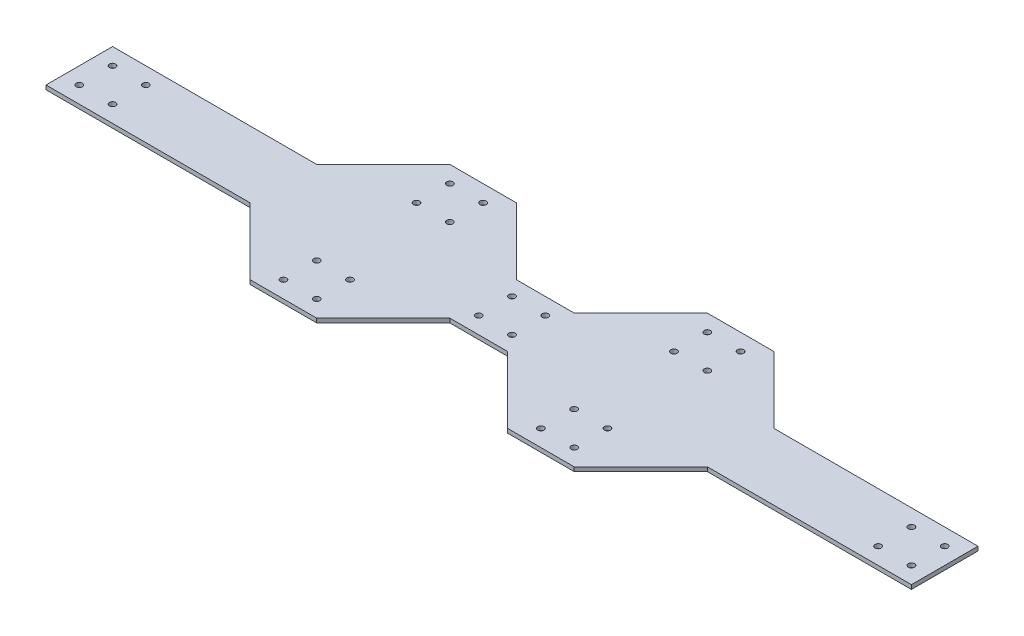
SolidWorks part; units mm, degrees
ref_plane "Front Plane" through (0, 0, 0) normal (0, 0, 1) x (1, 0, 0)
ref_plane "Top Plane" through (0, 0, 0) normal (0, 1, 0) x (1, 0, 0)
ref_plane "Right Plane" through (0, 0, 0) normal (1, 0, 0) x (0, 0, -1)
sketch "Sketch2" plane through (0, 0, 0) normal (0, 1, 0) x (1, 0, 0)
  line L0 (0, 0) -> (0, 50000) construction
  line L1 (22.0266, 25.4) -> (72.8266, 76.2)
  line L2 (72.8266, 76.2) -> (123.6266, 76.2)
  line L3 (123.6266, 76.2) -> (174.4266, 25.4)
  line L4 (174.4266, 25.4) -> (330.2, 25.4)
  line L5 (330.2, 25.4) -> (330.2, -25.4)
  line L6 (330.2, -25.4) -> (174.4266, -25.4)
  line L7 (174.4266, -25.4) -> (123.6266, -76.2)
  line L8 (123.6266, -76.2) -> (72.8266, -76.2)
  line L9 (72.8266, -76.2) -> (22.0266, -25.4)
  line L10 (22.0266, -25.4) -> (-22.0266, -25.4)
  line L11 (22.0266, 25.4) -> (-22.0266, 25.4)
  line L12 (-72.8266, -76.2) -> (-22.0266, -25.4)
  line L13 (-123.6266, -76.2) -> (-72.8266, -76.2)
  line L14 (-174.4266, -25.4) -> (-123.6266, -76.2)
  line L15 (-330.2, -25.4) -> (-174.4266, -25.4)
  line L16 (-330.2, 25.4) -> (-330.2, -25.4)
  line L17 (-174.4266, 25.4) -> (-330.2, 25.4)
  line L18 (-123.6266, 76.2) -> (-174.4266, 25.4)
  line L19 (-72.8266, 76.2) -> (-123.6266, 76.2)
  line L20 (-22.0266, 25.4) -> (-72.8266, 76.2)
  point P16 (0, 25.4)
  point P17 (0, -25.4)
  point P18 (330.2, 0)
  dimension "D1" = 152.4
  dimension "D2" = 660.4
  dimension "D3" = 50.8
  dimension "D4" = 72.8266
extrude "Boss-Extrude1" add sketch "Sketch2" along normal blind 3.175
sketch "Sketch3" plane through (0, 3.175, 0) normal (0, 1, 0) x (1, 0, 0)
  line L0 (-110.9266, 38.1) -> (-85.5266, 63.5) construction
  line L1 (-149.0266, 50.8) -> (-47.4266, 50.8) construction
  line L2 (-123.6266, 76.2) -> (-174.4266, 25.4) construction
  line L3 (-22.0266, 25.4) -> (-72.8266, 76.2) construction
  line L4 (0, 0) -> (-14.3721, 0) construction
  line L5 (0, 0) -> (0, 50000) construction
  line L6 (149.0266, 50.8) -> (47.4266, 50.8) construction
  line L7 (110.9266, 38.1) -> (85.5266, 63.5) construction
  line L10 (-330.2, 25.4) -> (-330.2, -25.4) construction
  circle A0 centre (-110.9266, 63.5) radius 2.3813
  circle A1 centre (-85.5266, 63.5) radius 2.3813
  circle A2 centre (-110.9266, 38.1) radius 2.3813
  circle A3 centre (-85.5266, 38.1) radius 2.3813
  circle A4 centre (-85.5266, -38.1) radius 2.3813
  circle A5 centre (-110.9266, -38.1) radius 2.3813
  circle A6 centre (-85.5266, -63.5) radius 2.3813
  circle A7 centre (-110.9266, -63.5) radius 2.3813
  circle A8 centre (110.9266, -63.5) radius 2.3813
  circle A9 centre (85.5266, -63.5) radius 2.3813
  circle A10 centre (110.9266, -38.1) radius 2.3813
  circle A11 centre (85.5266, -38.1) radius 2.3813
  circle A12 centre (85.5266, 38.1) radius 2.3813
  circle A13 centre (110.9266, 38.1) radius 2.3813
  circle A14 centre (85.5266, 63.5) radius 2.3813
  circle A15 centre (110.9266, 63.5) radius 2.3813
  circle A22 centre (-292.1, -12.7) radius 2.3813
  circle A23 centre (-317.5, -12.7) radius 2.3813
  circle A24 centre (-317.5, 12.7) radius 2.3813
  circle A25 centre (-292.1, 12.7) radius 2.3813
  circle A26 centre (292.1, 12.7) radius 2.3813
  circle A27 centre (317.5, 12.7) radius 2.3813
  circle A28 centre (317.5, -12.7) radius 2.3813
  circle A29 centre (292.1, -12.7) radius 2.3813
  circle A30 centre (-12.7, 12.7) radius 2.3813
  circle A31 centre (12.7, 12.7) radius 2.3813
  circle A32 centre (12.7, -12.7) radius 2.3813
  circle A33 centre (-12.7, -12.7) radius 2.3812
  point P16 (-98.2266, 50.8)
  point P17 (-98.2266, 50.8)
  point P28 (-98.2266, -50.8)
  point P50 (98.2266, -50.8)
  point P51 (98.2266, 50.8)
  point P67 (0, 0)
  dimension "D1" = 4.7625
  dimension "D7" = 4.7625
  dimension "D2" = 25.4
  dimension "D3" = 25.4
  dimension "D4" = 25.4
  dimension "D5" = 25.4
  dimension "D6" = 12.7
  dimension "D8" = 12.7
  dimension "D9" = 12.7
  dimension "D10" = 4
extrude "Cut-Extrude1" cut sketch "Sketch3" against normal through all both and the other way through all
